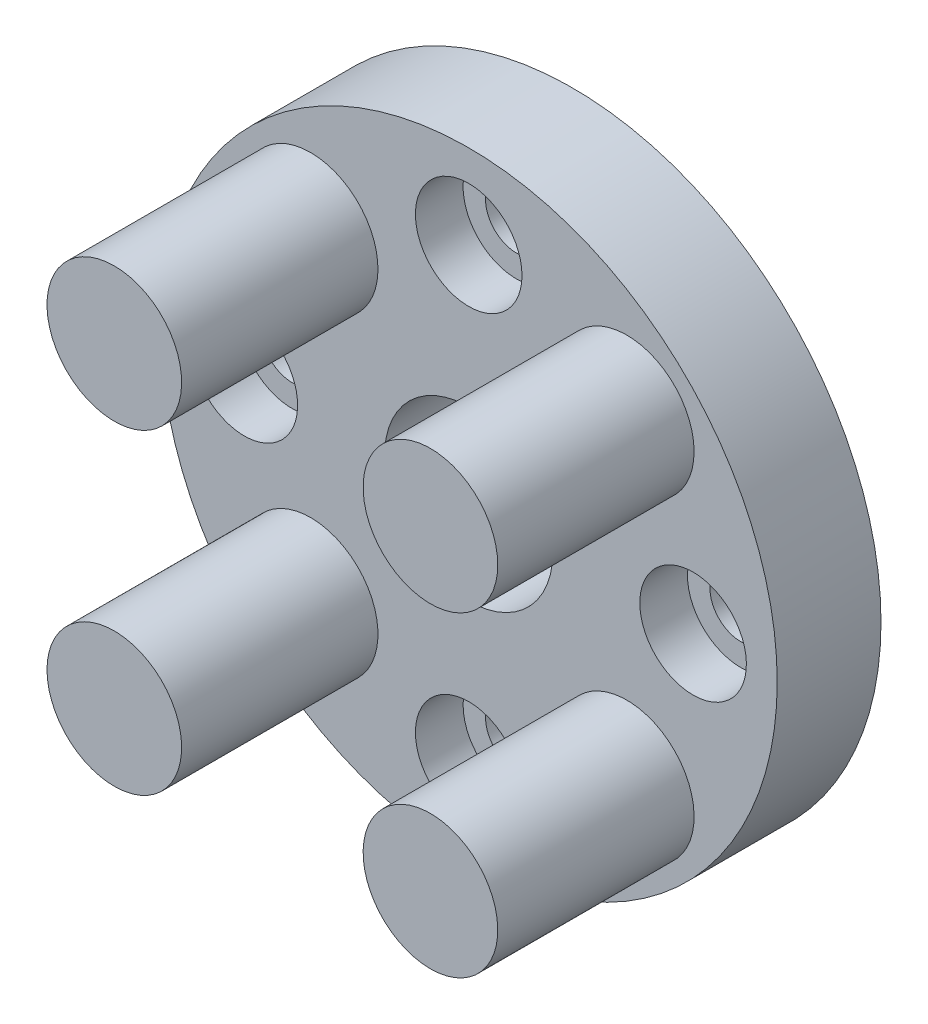
SolidWorks part; units mm, degrees
ref_plane "Front Plane" through (0, 0, 0) normal (0, 0, 1) x (1, 0, 0)
ref_plane "Top Plane" through (0, 0, 0) normal (0, 1, 0) x (1, 0, 0)
ref_plane "Right Plane" through (0, 0, 0) normal (1, 0, 0) x (0, 0, -1)
sketch "DynamixelHub" plane through (0, 0, 0) normal (0, 0, 1) x (1, 0, 0)
  circle A0 centre (0, 0) radius 11
  circle A1 centre (0, 0) radius 8 construction
  circle A3 centre (0, 0) radius 3
  circle A7 centre (0, 8) radius 1.1
  circle A8 centre (8, 0) radius 1.1
  circle A9 centre (0, -8) radius 1.1
  circle A10 centre (-8, 0) radius 1.1
  point P16 (0, 0)
  point P24 (0, 0)
  dimension "DynamixelHubDiameter" = 22
  dimension "DynamixelHubHolePositionDiameter" = 16
  dimension "DynamixelHubCenterHoleDiameter" = 6
  dimension "D2" = 4
  dimension "DynamixelHubHoleDrillDiameter" = 2.2
extrude "Hub" add sketch "DynamixelHub" along normal blind 3.7
sketch "Sketch2" plane through (0, 0, 3.7) normal (0, 0, 1) x (1, 0, 0)
  circle A0 centre (0, 8) radius 1.9
  dimension "DynamixelHubScrewLower" = 3.8
extrude "ScrewSlot" cut sketch "Sketch2" against normal blind 1.7
pattern_circular "ScrewSlots" count 4 over 360 about axis through (0, 0, 0) along (0, 0, 1) of "ScrewSlot"
sketch "Sketch3" plane through (0, 0, 3.7) normal (0, 0, 1) x (1, 0, 0)
  line L0 (0, 0) -> (5.6356, 5.6356) construction
  line L1 (0, 0) -> (0, 7.97) construction
  circle A0 centre (0, 0) radius 7.97 construction
  circle A1 centre (5.6356, 5.6356) radius 2.4
  dimension "D1" = 45
  dimension "LegoHoleSpacing" = 15.94
  dimension "D2" = 4.8
extrude "LegoPin" add sketch "Sketch3" along normal blind 7
pattern_circular "LegoPins" count 4 over 360 about axis through (0, 0, 0) along (0, 0, 1) of "LegoPin"
equation "\"DynamixelHubThickness\"= 4mm"
equation "\"DynamixelHubScrewTotalLength\" = 7.2mm"
equation "\"DynamixelHubScrewLength\"= \"DynamixelHubScrewTotalLength\" - 1.4mm"
equation "\"DynamixelHubScrewCapDiameter\"= 3.4mm"
equation "\"D1@Hub\"=\"DynamixelHubScrewTotalLength\"-\"DynamixelHubThickness\"+0.5"
equation "\"DynamixelHubScrewLower@Sketch2\"=\"DynamixelHubScrewCapDiameter\"+0.4"
equation "\"D1@ScrewSlot\" = \"DynamixelHubScrewTotalLength\" - \"DynamixelHubScrewLength\" + 0.3"
